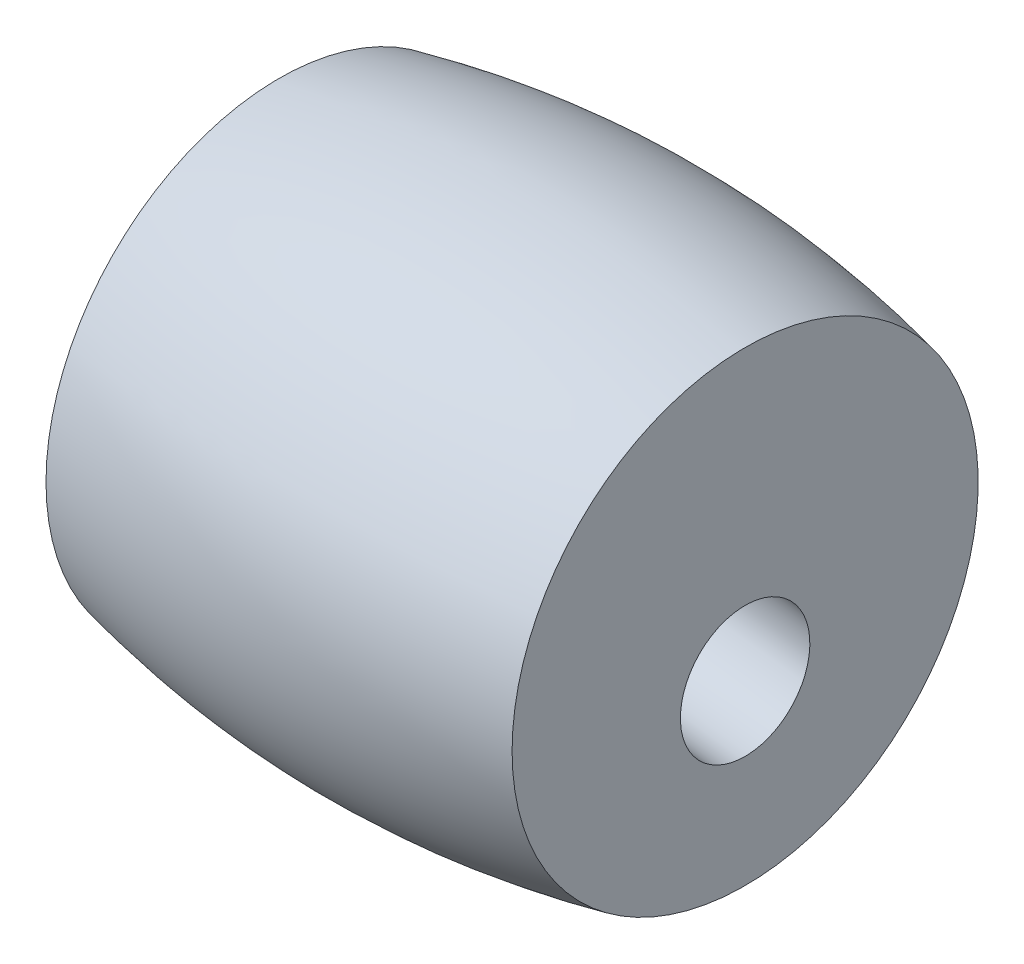
SolidWorks part; units mm, degrees
material "橡胶"
ref_plane "前视基准面" through (0, 0, 0) normal (0, 0, 1) x (1, 0, 0)
ref_plane "上视基准面" through (0, 0, 0) normal (0, 1, 0) x (1, 0, 0)
ref_plane "右视基准面" through (0, 0, 0) normal (1, 0, 0) x (0, 0, -1)
sketch "草图1" plane through (0, 0, 0) normal (0, 0, 1) x (1, 0, 0)
  line L0 (-9, 74) -> (-9, 65)
  line L1 (9, 65) -> (-9, 65)
  line L2 (9, 65) -> (9, 74)
  line L3 (9, 74) -> (-9, 74) construction
  line L4 (-1000, 65) -> (49000, 65) construction
  line L5 (0, -1000) -> (0, 49000) construction
  circle A0 centre (0, 0) radius 65 construction
  spline S0 degree 2 poles (-9, 74) (0, 76) (9, 74) knots 0 0 0 1 1 1
  dimension "D1" = 130
  dimension "D2" = 9
  dimension "D3" = 9
  dimension "D4" = 9
  dimension "D5" = 1
revolve "旋转1" add sketch "草图1" angle 360 about L4
sketch "草图2" plane through (0, 0, 0) normal (0, 0, 1) x (1, 0, 0)
  circle A0 centre (0, 0) radius 65
  dimension "D1" = 130
sketch "草图3" plane through (0, 0, 0) normal (0, 1, 0) x (1, 0, 0)
  line L0 (-65, 0) -> (65, 0) construction
  circle A0 centre (-63.4905, 0) radius 2.5
  dimension "D1" = 5
sweep "切除-扫描1" cut profiles "草图3" path "草图2"
sketch "草图4" plane through (0, 0, 0) normal (0, 0, 1) x (1, 0, 0)
  circle A0 centre (0, 0) radius 65
  dimension "D1" = 130
